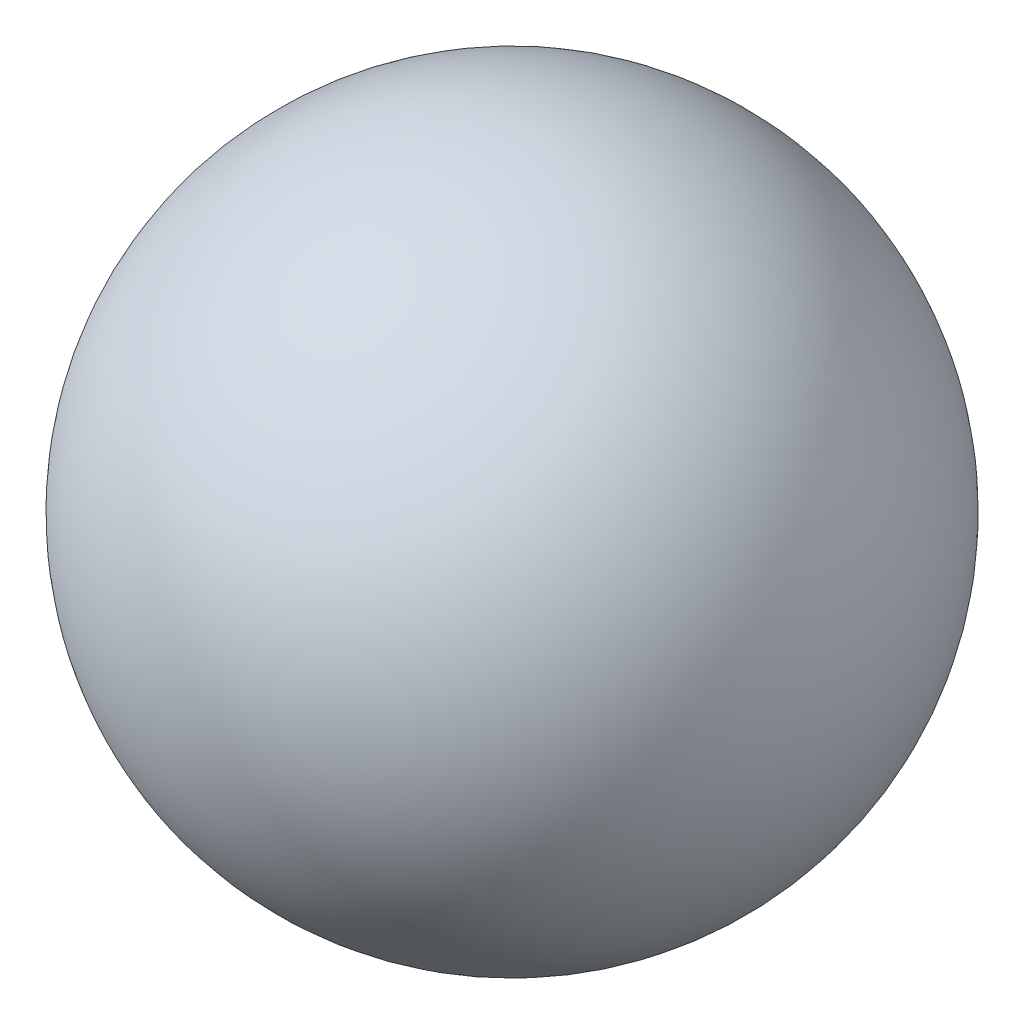
SolidWorks part; units mm, degrees
ref_plane "Front Plane" through (0, 0, 0) normal (0, 0, 1) x (1, 0, 0)
ref_plane "Top Plane" through (0, 0, 0) normal (0, 1, 0) x (1, 0, 0)
ref_plane "Right Plane" through (0, 0, 0) normal (1, 0, 0) x (0, 0, -1)
sketch "Sketch1" plane through (0, 0, 0) normal (0, 1, 0) x (1, 0, 0)
  line L0 (0, -15.1343) -> (0, 15.4997) construction
  line L1 (0, 7.62) -> (0, -7.62)
  arc A0 (0, -7.62) -> (0, 7.62) centre (0, 0) ccw
  dimension "D1" = 15.24
revolve "Revolve1" add sketch "Sketch1" angle 360 about L0
